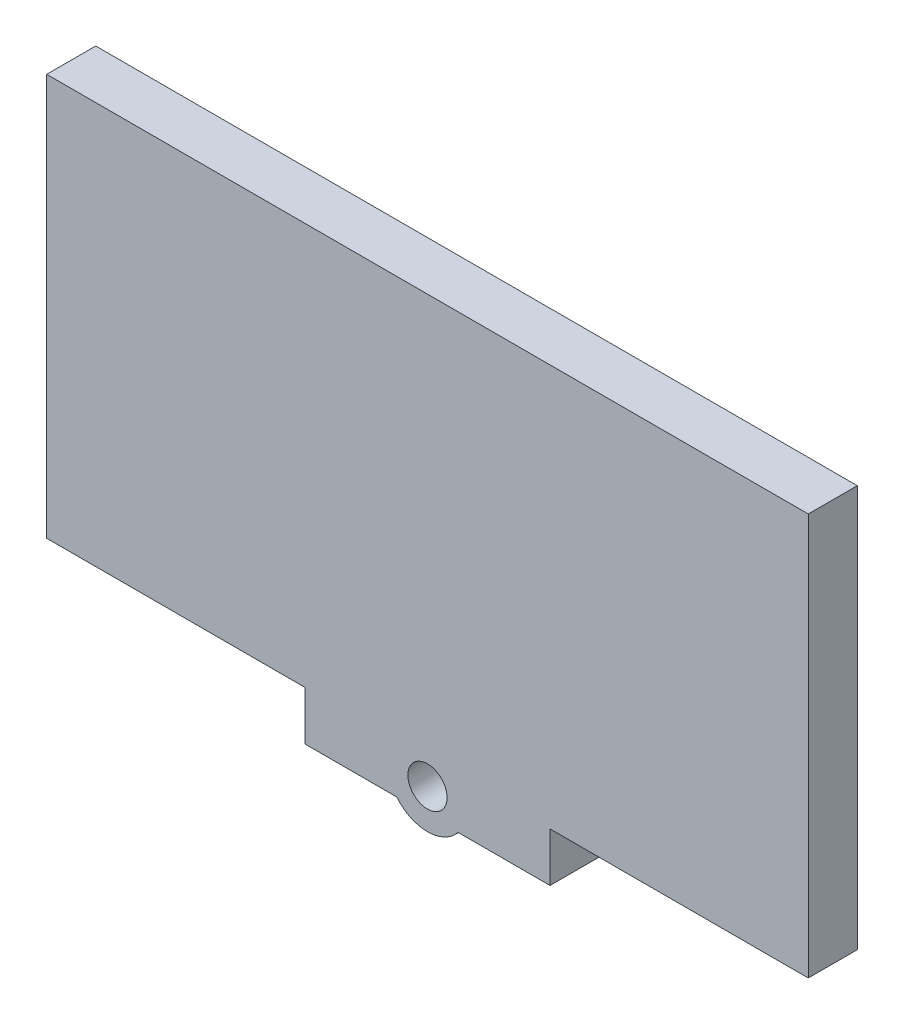
SolidWorks part; units mm, degrees
ref_plane "Front Plane" through (0, 0, 0) normal (0, 0, 1) x (1, 0, 0)
ref_plane "Top Plane" through (0, 0, 0) normal (0, 1, 0) x (1, 0, 0)
ref_plane "Right Plane" through (0, 0, 0) normal (1, 0, 0) x (0, 0, -1)
sketch "Sketch1" plane through (0, 0, 0) normal (0, 0, 1) x (1, 0, 0)
  line L1 (-38.85, 20.5) -> (38.85, 20.5)
  line L2 (-38.85, 20.5) -> (-38.85, -20.5)
  line L3 (-38.85, -20.5) -> (38.85, -20.5)
  line L4 (38.85, 20.5) -> (38.85, -20.5)
  dimension "D1" = 77.7
  dimension "D2" = 38.85
  dimension "D3" = 41
  dimension "D4" = 20.5
extrude "Boss-Extrude1" add sketch "Sketch1" along normal blind 5
sketch "Sketch2" plane through (0, 0, 5) normal (0, 0, 1) x (1, 0, 0)
  line L0 (-38.85, -20.5) -> (38.85, -20.5) construction
  line L1 (-12.5, -20.5) -> (12.5, -20.5)
  line L2 (-12.5, -20.5) -> (-12.5, -25.5)
  line L3 (-12.5, -25.5) -> (12.5, -25.5)
  line L4 (12.5, -20.5) -> (12.5, -25.5)
  line L5 (-38.85, 20.5) -> (-38.85, -20.5) construction
  dimension "D1" = 25
  dimension "D2" = 26.35
  dimension "D3" = 5
extrude "Boss-Extrude2" add sketch "Sketch2" against normal blind 5
sketch "Sketch3" plane through (0, 0, 5) normal (0, 0, 1) x (1, 0, 0)
  circle A0 centre (-0.0015, -23) radius 2
  dimension "D1" = 4
extrude "Cut-Extrude1" cut sketch "Sketch3" against normal blind 5
sketch "Sketch4" plane through (0, 0, 5) normal (0, 0, 1) x (1, 0, 0)
  circle A0 centre (-0.0015, -23) radius 2
  circle A1 centre (-0.0015, -23) radius 4
  dimension "D1" = 8
extrude "Boss-Extrude3" add sketch "Sketch4" against normal blind 5
